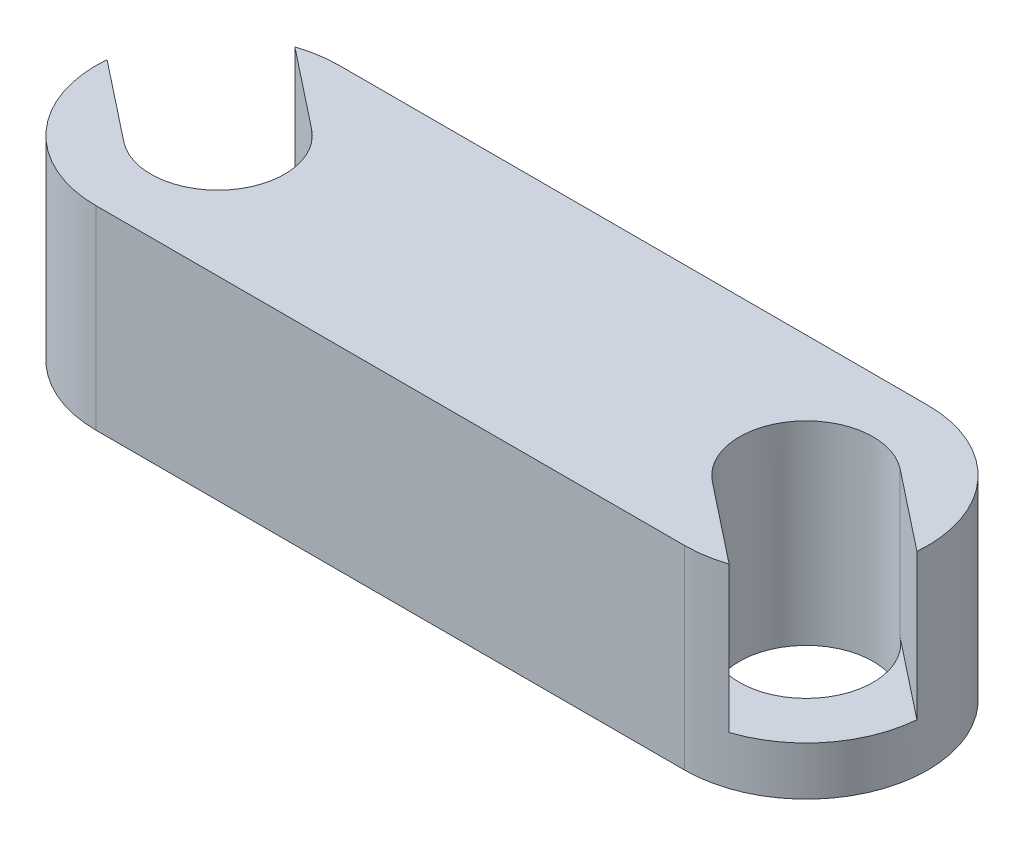
SolidWorks part; units mm, degrees
ref_plane "Front Plane" through (0, 0, 0) normal (0, 0, 1) x (1, 0, 0)
ref_plane "Top Plane" through (0, 0, 0) normal (0, 1, 0) x (1, 0, 0)
ref_plane "Right Plane" through (0, 0, 0) normal (1, 0, 0) x (0, 0, -1)
sketch "Sketch1" plane through (0, 0, 0) normal (0, 1, 0) x (1, 0, 0)
  line L0 (-7.7125, 6.5) -> (16.4949, 6.5)
  line L1 (-7.7125, -3.5) -> (16.4949, -3.5)
  arc A0 (-7.7125, 6.5) -> (-7.7125, -3.5) centre (-7.7125, 1.5) ccw
  arc A1 (16.4949, -3.5) -> (16.4949, 6.5) centre (16.4949, 1.5) ccw
  circle A2 centre (-7.7125, 1.5) radius 2.75
  circle A3 centre (16.4949, 1.5) radius 2.75
  dimension "D3" = 5.5
  dimension "D4" = 5.5
  dimension "D5" = 5
  dimension "D2" = 24.2074
extrude "Boss-Extrude1" add sketch "Sketch1" along normal blind 8
sketch "Sketch2" plane through (0, 8, 0) normal (0, 1, 0) x (1, 0, 0)
  line L0 (4.3912, 6.5) -> (4.3912, -6.8516) construction
  line L5 (16.4949, 6.5) -> (-7.7125, 6.5) construction
  line L10 (16.4949, 1.5) -> (-7.7125, 1.5) construction
  line L11 (18.1989, 3.6584) -> (14.7909, -0.6584)
  line L12 (18.1989, 3.6584) -> (28.1298, -4.1817)
  line L13 (14.7909, -0.6584) -> (24.7217, -8.4986)
  line L14 (28.1298, -4.1817) -> (24.7217, -8.4986)
  line L15 (21.4949, 1.5) -> (27.9244, 1.5) construction
  line L16 (-6.0085, -0.6584) -> (-15.9394, -8.4986) construction
  line L17 (-19.3474, -4.1817) -> (-15.9394, -8.4986) construction
  line L18 (-9.4165, 3.6584) -> (-19.3474, -4.1817) construction
  line L19 (-9.4165, 3.6584) -> (-6.0085, -0.6584) construction
  line L20 (-9.4165, -0.6584) -> (-6.0085, 3.6584)
  line L21 (-9.4165, -0.6584) -> (-19.3474, 7.1817)
  line L22 (-19.3474, 7.1817) -> (-15.9394, 11.4986)
  line L23 (-6.0085, 3.6584) -> (-15.9394, 11.4986)
  circle A1 centre (16.4949, 1.5) radius 2.75 construction
  arc A2 (16.4949, -3.5) -> (16.4949, 6.5) centre (16.4949, 1.5) ccw construction
  dimension "D2" = 12.6527
  dimension "D3" = 38.29
extrude "Cut-Extrude1" cut sketch "Sketch2" against normal blind 6
